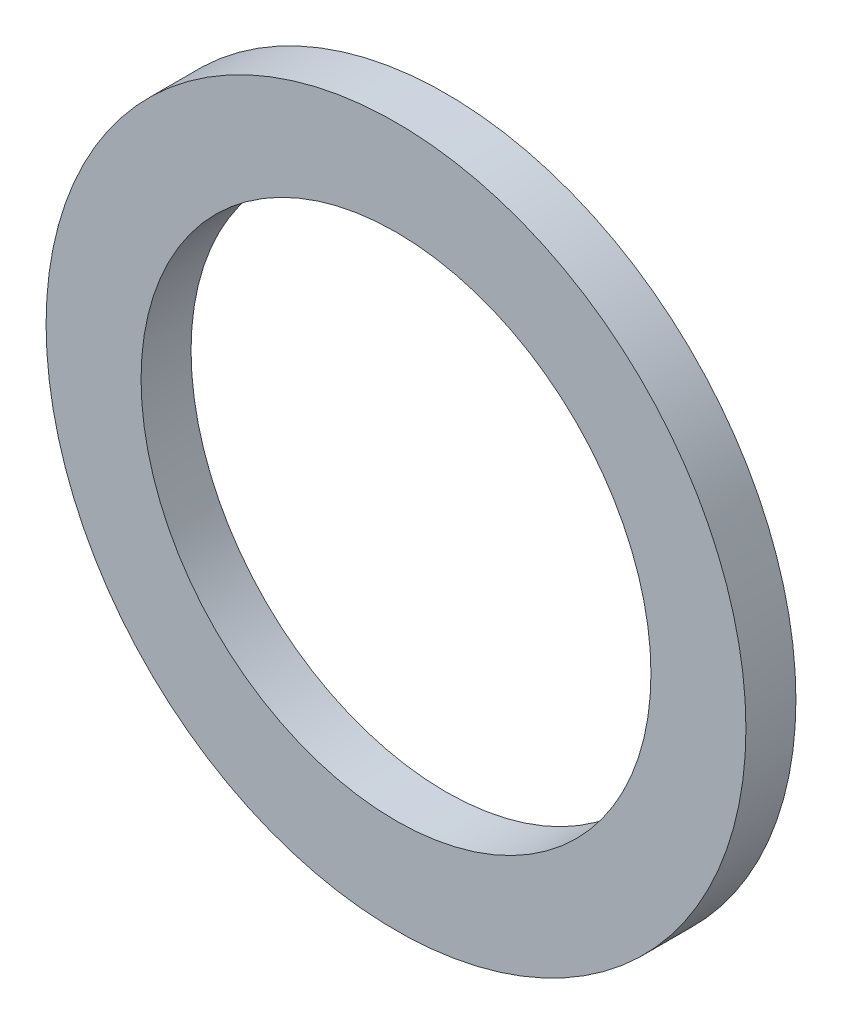
SolidWorks part; units mm, degrees
material "Медь"
ref_plane "Спереди" through (0, 0, 0) normal (0, 0, 1) x (1, 0, 0)
ref_plane "Сверху" through (0, 0, 0) normal (0, 1, 0) x (1, 0, 0)
ref_plane "Справа" through (0, 0, 0) normal (1, 0, 0) x (0, 0, -1)
other "Configuration Table"
sketch "Эскиз1" plane through (0, 0, 0) normal (0, 0, 1) x (1, 0, 0)
  circle A0 centre (0, 0) radius 5.1
  circle A1 centre (0, 0) radius 7
  dimension "D1" = 10.2
  dimension "D2" = 14
extrude "Бобышка-Вытянуть1" add sketch "Эскиз1" along normal blind 1
